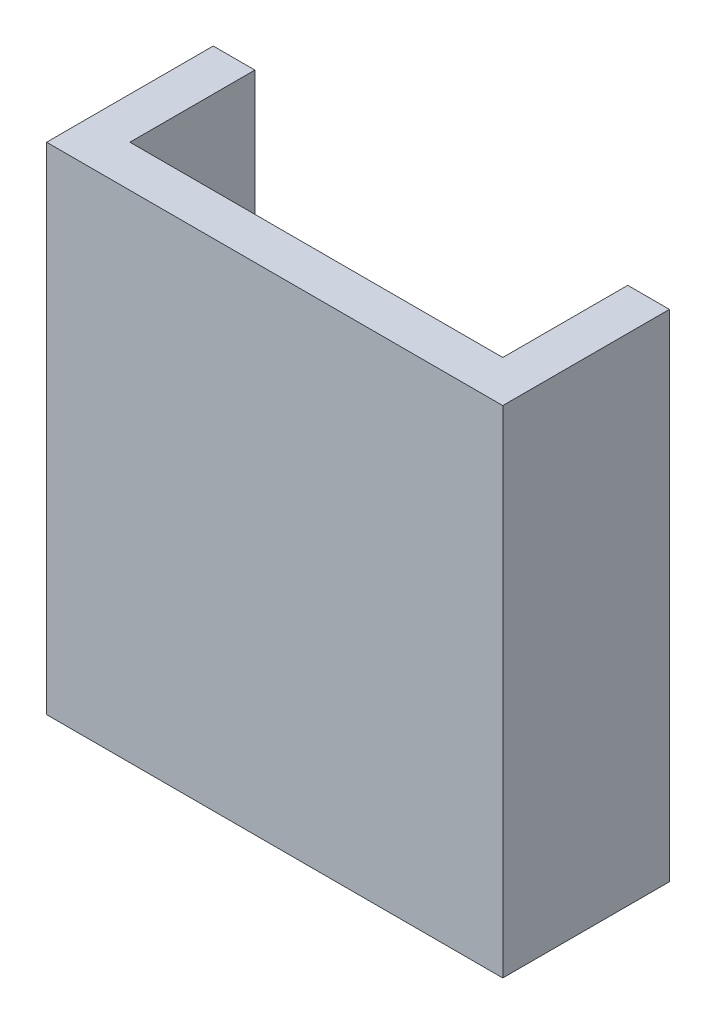
SolidWorks part; units mm, degrees
ref_plane "前基準面" through (0, 0, 0) normal (0, 0, 1) x (1, 0, 0)
ref_plane "上基準面" through (0, 0, 0) normal (0, 1, 0) x (1, 0, 0)
ref_plane "右基準面" through (0, 0, 0) normal (1, 0, 0) x (0, 0, -1)
sketch "草圖1" plane through (0, 0, 0) normal (0, 0, 1) x (1, 0, 0)
  line L1 (-4.475, 5.45) -> (4.475, 5.45)
  line L2 (-4.475, 5.45) -> (-4.475, -5.45)
  line L3 (-4.475, -5.45) -> (4.475, -5.45)
  line L4 (4.475, 5.45) -> (4.475, -5.45)
sketch "草圖2" plane through (0, 0, 0) normal (0, 0, 1) x (1, 0, 0)
  line L1 (-5.475, 5.45) -> (5.475, 5.45)
  line L2 (-5.475, 5.45) -> (-5.475, -6.45)
  line L3 (-5.475, -6.45) -> (5.475, -6.45)
  line L4 (5.475, 5.45) -> (5.475, -6.45)
extrude "填料-伸長2" add sketch "草圖2" along normal blind 4
extrude "除料-伸長1" cut sketch "草圖1" along normal blind 3
